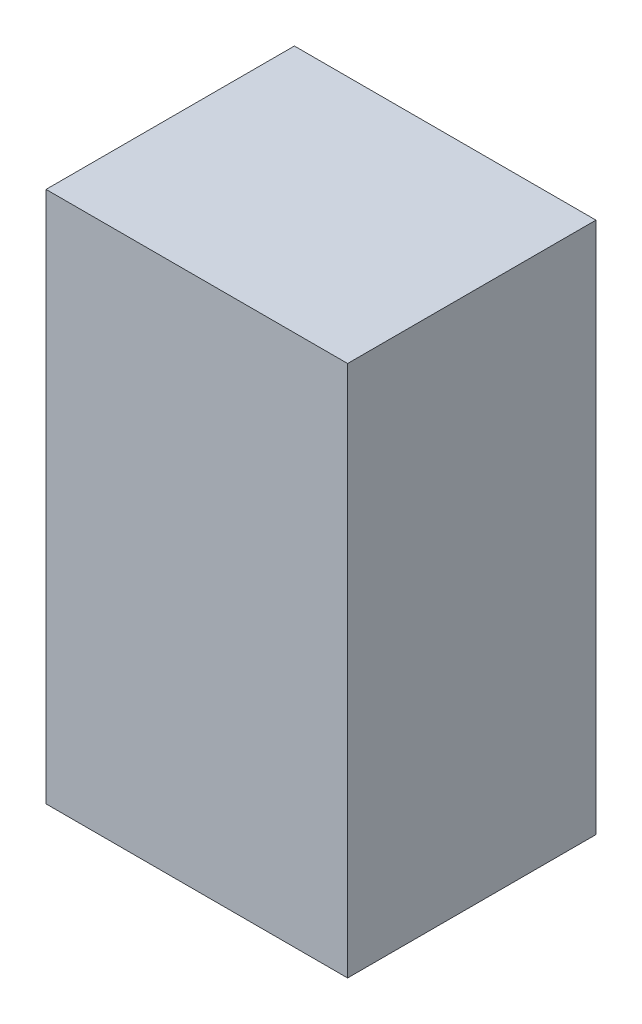
SolidWorks part; units mm, degrees
ref_plane "Front Plane" through (0, 0, 0) normal (0, 0, 1) x (1, 0, 0)
ref_plane "Top Plane" through (0, 0, 0) normal (0, 1, 0) x (1, 0, 0)
ref_plane "Right Plane" through (0, 0, 0) normal (1, 0, 0) x (0, 0, -1)
sketch "Sketch1" plane through (0, 0, 0) normal (0, 0, 1) x (1, 0, 0)
  line L0 (0.85, 1.5) -> (0.85, -1.5)
  line L1 (0.85, -1.5) -> (-0.85, -1.5)
  line L2 (-0.85, -1.5) -> (-0.85, 1.5)
  line L3 (-0.85, 1.5) -> (0.85, 1.5)
extrude "Component_Outline" add sketch "Sketch1" along normal blind 1.4 separate body
sketch3d "3DSketch1"
  line L0 (0, 0, 0) -> (1, 0, 0)
  line L1 (0, 0, 0) -> (0, 1, 0)
  line L2 (0, 0, 0) -> (0, 0, 1)
  point P0 (0, 0, 0)
